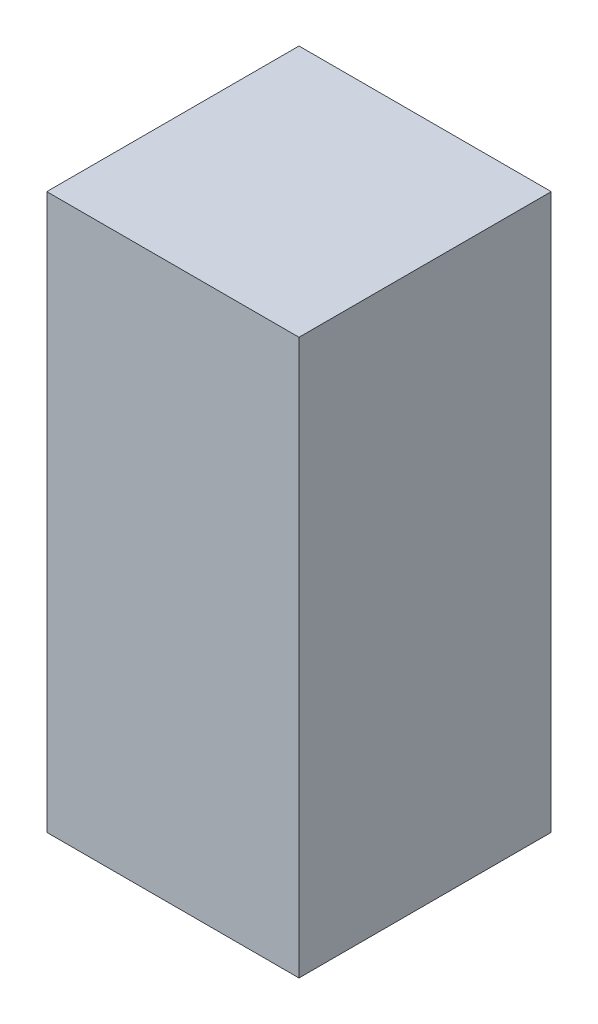
SolidWorks part; units mm, degrees
ref_plane "Front Plane" through (0, 0, 0) normal (0, 0, 1) x (1, 0, 0)
ref_plane "Top Plane" through (0, 0, 0) normal (0, 1, 0) x (1, 0, 0)
ref_plane "Right Plane" through (0, 0, 0) normal (1, 0, 0) x (0, 0, -1)
sketch "Sketch1" plane through (0, 0, 0) normal (0, 1, 0) x (1, 0, 0)
  line L1 (-12.5, 12.5) -> (12.5, 12.5)
  line L2 (-12.5, 12.5) -> (-12.5, -12.5)
  line L3 (-12.5, -12.5) -> (12.5, -12.5)
  line L4 (12.5, 12.5) -> (12.5, -12.5)
  line L5 (-12.5, 12.5) -> (12.5, -12.5) construction
  line L6 (-12.5, -12.5) -> (12.5, 12.5) construction
  point P0 (0, 0)
  dimension "D1" = 25
  dimension "D2" = 25
extrude "Boss-Extrude1" add sketch "Sketch1" along normal blind 55 contours L2 L3 L4 L1
